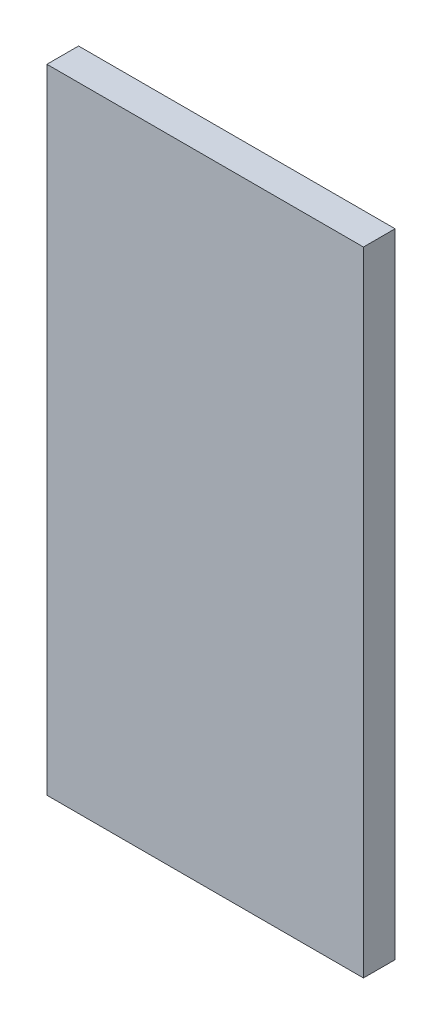
SolidWorks part; units mm, degrees
ref_plane "Front Plane" through (0, 0, 0) normal (0, 0, 1) x (1, 0, 0)
ref_plane "Top Plane" through (0, 0, 0) normal (0, 1, 0) x (1, 0, 0)
ref_plane "Right Plane" through (0, 0, 0) normal (1, 0, 0) x (0, 0, -1)
sketch "Sketch2" plane through (0, 0, 0) normal (0, 0, 1) x (1, 0, 0)
  line L0 (0, 0) -> (1000, 0)
  line L1 (1000, 0) -> (1000, 2000)
  line L2 (1000, 2000) -> (0, 2000)
  line L3 (0, 2000) -> (0, 0)
extrude "Boss-Extrude2" add sketch "Sketch2" along normal blind 100
